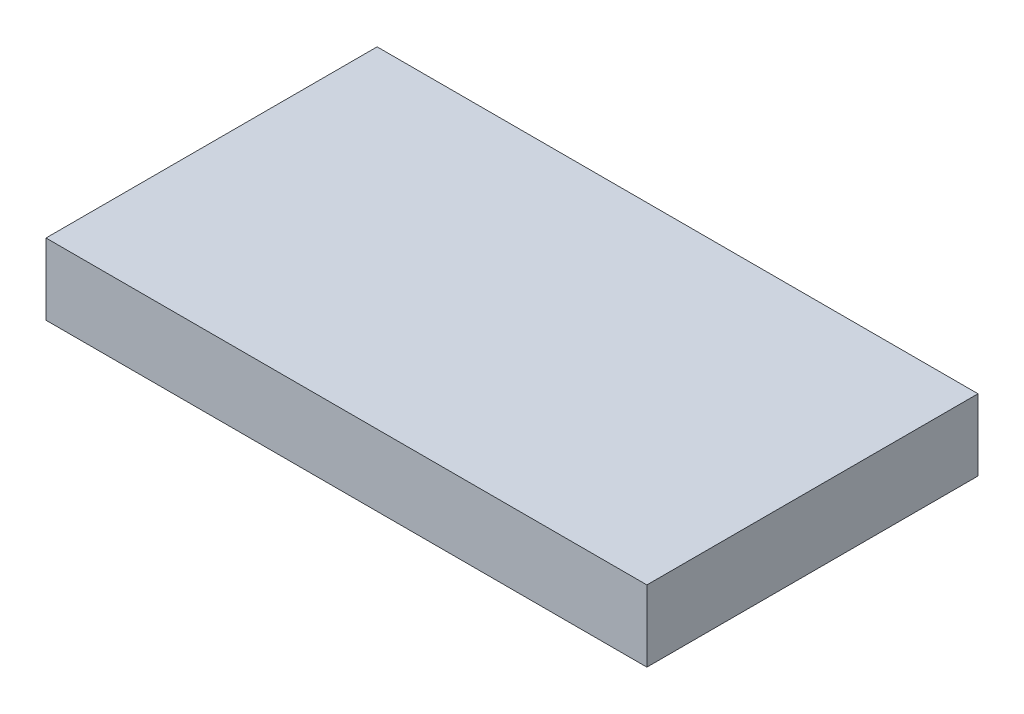
SolidWorks part; units mm, degrees
ref_plane "정면" through (0, 0, 0) normal (0, 0, 1) x (1, 0, 0)
ref_plane "윗면" through (0, 0, 0) normal (0, 1, 0) x (1, 0, 0)
ref_plane "우측면" through (0, 0, 0) normal (1, 0, 0) x (0, 0, -1)
sketch "스케치1" plane through (0, 0, 0) normal (0, 1, 0) x (1, 0, 0)
  line L1 (-42.1714, 23.2373) -> (42.1714, 23.2373)
  line L2 (-42.1714, 23.2373) -> (-42.1714, -23.2373)
  line L3 (-42.1714, -23.2373) -> (42.1714, -23.2373)
  line L4 (42.1714, 23.2373) -> (42.1714, -23.2373)
  line L5 (-42.1714, 23.2373) -> (42.1714, -23.2373) construction
  line L6 (-42.1714, -23.2373) -> (42.1714, 23.2373) construction
  point P0 (0, 0)
extrude "보스-돌출1" add sketch "스케치1" along normal blind 10
sketch "스케치5" plane through (0, 0, 0) normal (0, 0, 1) x (1, 0, 0)
  line L0 (0, -2.5) -> (0, 2.5)
  arc A0 (0, 2.5) -> (0, -2.5) centre (0, 0) ccw
revolve "컷-회전3" cut sketch "스케치5" angle 360 about L0
sketch "스케치6" plane through (0, 0, 0) normal (0, -1, 0) x (1, 0, 0)
  line L0 (0, 0) -> (-42.1714, 0)
  line L1 (-42.1714, -23.2373) -> (-42.1714, 23.2373) construction
  line L2 (-42.1714, 0) -> (42.1714, 0)
  line L3 (42.1714, 23.2373) -> (42.1714, -23.2373) construction
pattern_linear "선형 패턴3" count 4 spacing 10 along (-1, 0, 0) of "컷-회전3"
pattern_linear "선형 패턴4" count 4 spacing 10 along (1, 0, 0) of "컷-회전3"
ref_plane "평면1" through (0, 0, 15) normal (0, 0, 1) x (1, 0, 0)
sketch "스케치8" plane through (0, 0, 15) normal (0, 0, 1) x (1, 0, 0)
  line L0 (0, 2.5) -> (0, -2.5)
  arc A0 (0, 2.5) -> (0, -2.5) centre (0, 0) ccw
revolve "컷-회전4" cut sketch "스케치8" angle 360 about L0
sketch "스케치9" plane through (0, 0, 0) normal (0, -1, 0) x (1, 0, 0)
  line L0 (0, 15) -> (42.1714, 15)
  line L1 (42.1714, 23.2373) -> (42.1714, -23.2373) construction
  line L2 (42.1714, 15) -> (-42.1714, 15)
  line L3 (-42.1714, -23.2373) -> (-42.1714, 23.2373) construction
pattern_linear "선형 패턴5" count 4 spacing 10 along (1, 0, 0) of "컷-회전4"
pattern_linear "선형 패턴6" count 4 spacing 10 along (-1, 0, 0) of "컷-회전4"
mirror "대칭 복사1" about plane through (0, 0, 0) normal (0, 0, 1) of "선형 패턴6", "컷-회전4", "선형 패턴5"
